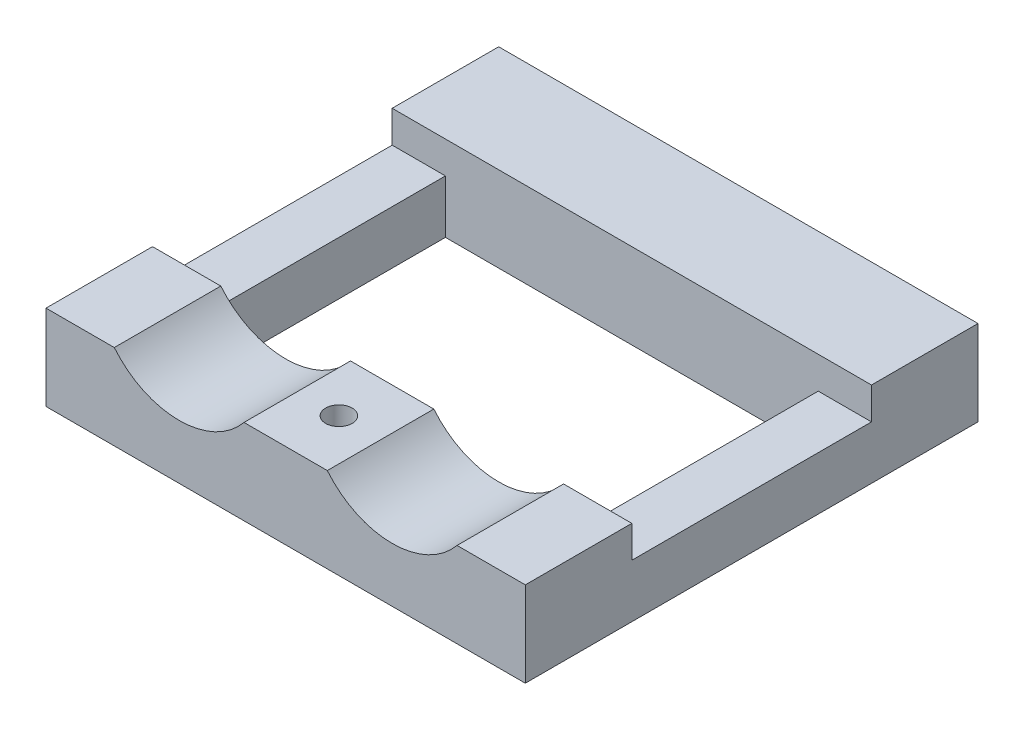
SolidWorks part; units mm, degrees
ref_plane "Front Plane" through (0, 0, 0) normal (0, 0, 1) x (1, 0, 0)
ref_plane "Top Plane" through (0, 0, 0) normal (0, 1, 0) x (1, 0, 0)
ref_plane "Right Plane" through (0, 0, 0) normal (1, 0, 0) x (0, 0, -1)
sketch "Sketch4" plane through (0, 0, 0) normal (0, 0, 1) x (1, 0, 0)
  line L1 (0, 0) -> (57.15, 0)
  line L2 (0, 0) -> (0, 10.16)
  line L3 (0, 10.16) -> (57.15, 10.16)
  line L4 (57.15, 0) -> (57.15, 10.16)
  dimension "D1" = 10.16
  dimension "D2" = 57.15
extrude "Boss-Extrude1" add sketch "Sketch4" along normal blind 12.7
sketch "Sketch5" plane through (0, 0, 12.7) normal (0, 0, 1) x (1, 0, 0)
  line L1 (0, 10.16) -> (15.875, 10.16) construction
  line L2 (0, 0) -> (57.15, 0) construction
  line L3 (57.15, 10.16) -> (0, 10.16) construction
  line L4 (15.875, 10.16) -> (15.875, 16.5) construction
  line L5 (41.275, 16.5) -> (41.275, 10.16) construction
  line L6 (41.275, 10.16) -> (57.15, 10.16) construction
  circle A0 centre (15.875, 16.5) radius 10
  circle A1 centre (41.275, 16.5) radius 10
  dimension "D3" = 20
  dimension "D1" = 25.4
  dimension "D4" = 16.5
extrude "Cut-Extrude1" cut sketch "Sketch5" against normal through all
sketch "Sketch8" plane through (0, 10.16, 0) normal (0, 1, 0) x (1, 0, 0)
  line L0 (23.6083, 0) -> (23.6083, -12.7) construction
  line L1 (33.5417, 0) -> (23.6083, 0) construction
  circle A0 centre (28.575, -6.35) radius 1.5875
  point P5 (23.6083, -6.35)
  point P9 (28.575, 0)
  dimension "D1" = 3.175
extrude "Cut-Extrude3" cut sketch "Sketch8" against normal through all
sketch "Sketch9" plane through (0, 0, 0) normal (0, 0, -1) x (-1, 0, 0)
  line L0 (-57.15, 0) -> (-57.15, 6.35)
  line L1 (-57.15, 6.35) -> (-50.8, 6.35)
  line L2 (-50.8, 6.35) -> (-50.8, 0)
  line L3 (0, 0) -> (-57.15, 0) construction
  line L4 (-50.8, 0) -> (-57.15, 0)
  line L5 (0, 0) -> (0, 6.35)
  line L6 (0, 6.35) -> (-6.35, 6.35)
  line L7 (-6.35, 6.35) -> (-6.35, 0)
  line L8 (-6.35, 0) -> (0, 0)
  point P3 (0, 0)
  point P6 (0, 0)
  point P13 (0, 0)
  point P17 (0, 0)
  dimension "D1" = 6.35
  dimension "D2" = 6.35
extrude "Boss-Extrude2" add sketch "Sketch9" along normal blind 28.575
sketch "Sketch11" plane through (0, 0, -28.575) normal (0, 0, -1) x (-1, 0, 0)
  line L1 (-57.15, 0) -> (0, 0)
  line L2 (-57.15, 0) -> (-57.15, 10.16)
  line L3 (-57.15, 10.16) -> (0, 10.16)
  line L4 (0, 0) -> (0, 10.16)
  point P6 (0, 0)
  point P7 (0, 0)
extrude "Boss-Extrude3" add sketch "Sketch11" along normal blind 12.7
